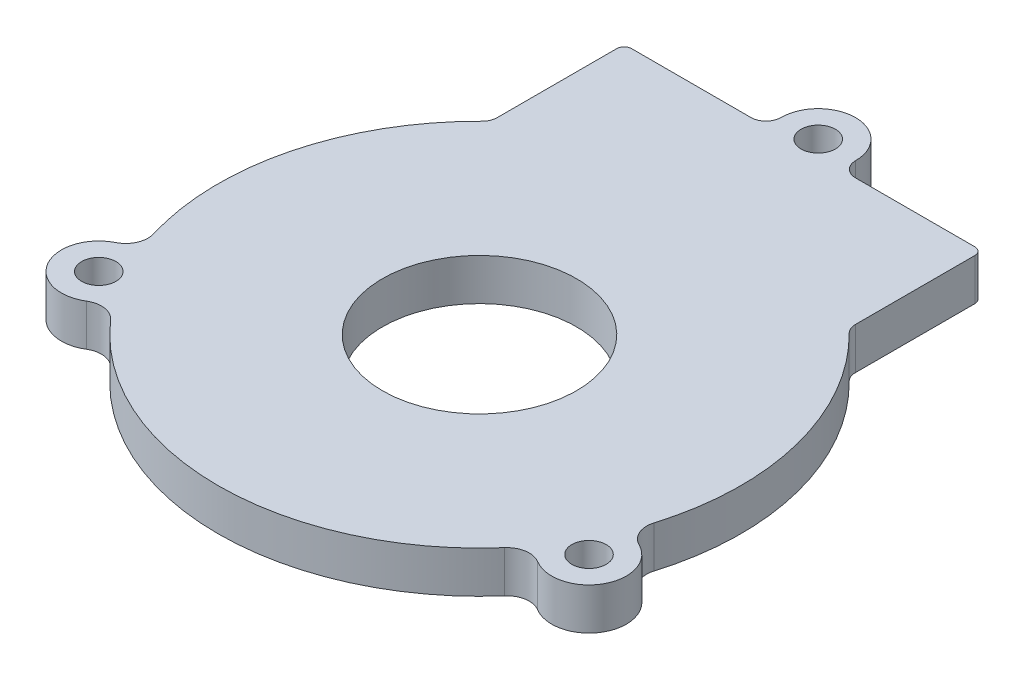
SolidWorks part; units mm, degrees
ref_plane "Front Plane" through (0, 0, 0) normal (0, 0, 1) x (1, 0, 0)
ref_plane "Top Plane" through (0, 0, 0) normal (0, 1, 0) x (1, 0, 0)
ref_plane "Right Plane" through (0, 0, 0) normal (1, 0, 0) x (0, 0, -1)
sketch "Sketch1" plane through (0, 0, 0) normal (0, 1, 0) x (1, 0, 0)
  line L2 (32.785, 0) -> (32.785, 24.2952) construction
  line L7 (32.785, 0) -> (32.785, 18.8) construction
  line L10 (32.785, 66.7015) -> (56.765, 66.7015) construction
  line L11 (32.785, 66.7015) -> (32.785, 59.7015) construction
  line L12 (32.785, 59.7015) -> (56.765, 59.7015) construction
  line L13 (56.765, 66.7015) -> (56.765, 59.7015) construction
  line L15 (56.765, 66.7015) -> (8.805, 66.7015)
  line L16 (56.765, 66.7015) -> (56.765, 41.7015)
  line L17 (56.765, 41.7015) -> (8.805, 41.7015)
  line L18 (8.805, 66.7015) -> (8.805, 41.7015)
  circle A0 centre (32.785, 23.3515) radius 35
  circle A1 centre (65.6, 5.2015) radius 5
  circle A4 centre (-0.03, 5.2015) radius 5
  circle A6 centre (-0.03, 5.2015) radius 2.3
  circle A7 centre (65.6, 5.2015) radius 2.3
  circle A8 centre (32.785, 23.3515) radius 13
  circle A9 centre (32.785, 68.7015) radius 2.3
  circle A10 centre (32.785, 68.7015) radius 5
  point P7 (32.785, 0)
  dimension "D1" = 7
  dimension "D5" = 43.35
  dimension "D7" = 37.5
  dimension "D10" = 4.6
  dimension "D11" = 2
  dimension "D13" = 10
  dimension "D2" = 23.98
  dimension "D3" = 47.96
  dimension "D4" = 25
  dimension "D6" = 37.5
  dimension "D8" = 61.5
  dimension "D9" = 61.5
  dimension "D12" = 0
extrude "Boss-Extrude3" add sketch "Sketch1" along normal blind 5.588 contours A4 | A1 | A0 | L15 L18 L17 L16 | A10 | A6 | A7 | A8
hole_wizard "Ø4.6 (4.6) Diameter Hole1" positions "Sketch4" profile "Sketch5" hole size "Ø4.6" standard "ANSI Metric" end condition through all
sketch "Sketch4" plane through (0, 5.588, 0) normal (0, 1, 0) x (1, 0, 0)
  point P0 (32.785, 68.7015)
sketch "Sketch5" plane through (32.785, 5.588, -68.7015) normal (1, 0, 0) x (0, 0, 1)
  line L0 (0, 0) -> (0, 5.588)
  line L1 (0, 5.588) -> (2.3, 5.588)
  line L2 (2.3, 5.588) -> (2.3, 0)
  line L5 (2.3, 0) -> (0, 0)
  line L11 (0, -6.35) -> (0, 107.95) construction
  dimension "Thru Hole Dia." = 4.6
  dimension "Thru Hole Depth" = 5.588
fillet "Fillet1" radius 3 4 edges at (65.2147, 2.794, -10.1866) (61.1725, 2.794, -2.8783) (4.3975, 2.794, -2.8783) (0.3553, 2.794, -10.1866)
fillet "Fillet2" radius 2 2 edges at (28.2024, 2.794, -66.7015) (37.3676, 2.794, -66.7015)
fillet "Fillet3" radius 2 2 edges at (56.765, 2.794, -48.8458) (8.805, 2.794, -48.8458)
fillet "Fillet4" radius 1 2 edges at (8.805, 2.794, -66.7015) (56.765, 2.794, -66.7015)
